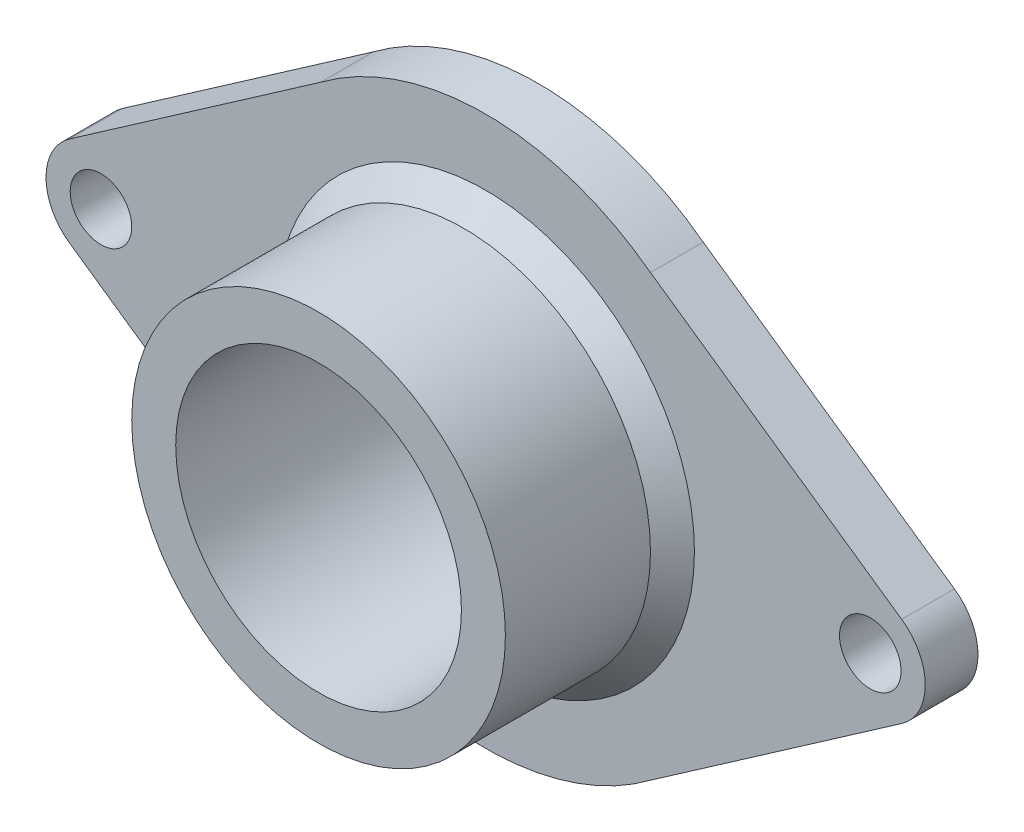
SolidWorks part; units mm, degrees
material "Gray Cast Iron (SN)"
ref_plane "Front Plane" through (0, 0, 0) normal (0, 0, 1) x (1, 0, 0)
ref_plane "Top Plane" through (0, 0, 0) normal (0, 1, 0) x (1, 0, 0)
ref_plane "Right Plane" through (0, 0, 0) normal (1, 0, 0) x (0, 0, -1)
sketch "Sketch1" plane through (0, 0, 0) normal (0, 0, 1) x (1, 0, 0)
  circle A0 centre (0, 0) radius 32.5
  circle A1 centre (0, 0) radius 42.5
  dimension "D1" = 85
  dimension "D2" = 65
extrude "Boss-Extrude1" add sketch "Sketch1" along normal blind 50
sketch "Sketch2" plane through (0, 0, 0) normal (0, 0, -1) x (-1, 0, 0)
  line L1 (-37.5, -50) -> (-94.6371, -10.2621)
  line L2 (-37.5, 50) -> (-94.6371, 10.2621)
  line L4 (37.5, -50) -> (94.6371, -10.2621)
  line L5 (37.5, 50) -> (94.6371, 10.2621)
  arc A1 (37.5, 50) -> (-37.5, 50) centre (0, 0) ccw
  arc A2 (-94.6371, 10.2621) -> (-94.6371, -10.2621) centre (-87.5, 0) ccw
  arc A3 (94.6371, -10.2621) -> (94.6371, 10.2621) centre (87.5, 0) ccw
  arc A4 (-37.5, -50) -> (37.5, -50) centre (0, 0) ccw
  circle A6 centre (0, 0) radius 42.5
  dimension "D1" = 125
  dimension "D4" = 25
  dimension "25" = 25
extrude "Boss-Extrude2" add sketch "Sketch2" against normal blind 12
sketch "Sketch3" plane through (0, 0, 0) normal (0, 0, -1) x (-1, 0, 0)
  circle A0 centre (87.5, 0) radius 7
  circle A1 centre (-87.5, 0) radius 7
  dimension "D1" = 14
  dimension "D2" = 14
extrude "Cut-Extrude1" cut sketch "Sketch3" against normal through all both and the other way through all
chamfer "Chamfer1" distance 5 angle 45 1 edges at (-42.5, 0, 12)
